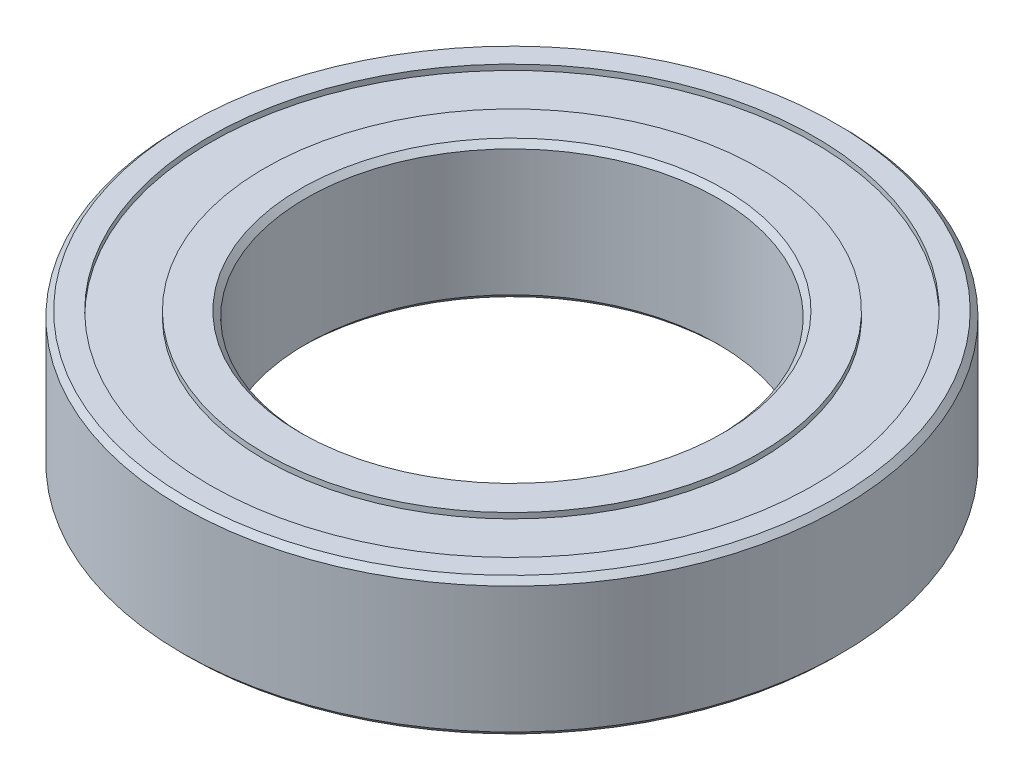
SolidWorks part; units mm, degrees
ref_plane "Front Plane" through (0, 0, 0) normal (0, 0, 1) x (1, 0, 0)
ref_plane "Top Plane" through (0, 0, 0) normal (0, 1, 0) x (1, 0, 0)
ref_plane "Right Plane" through (0, 0, 0) normal (1, 0, 0) x (0, 0, -1)
sketch "Sketch1" plane through (0, 0, 0) normal (0, 1, 0) x (1, 0, 0)
  circle A0 centre (0, 0) radius 12
  circle A1 centre (0, 0) radius 7.5
  dimension "D1" = 24
  dimension "D2" = 15
extrude "Boss-Extrude1" add sketch "Sketch1" along normal blind 5
sketch "Sketch2" plane through (0, 5, 0) normal (0, 1, 0) x (1, 0, 0)
  circle A0 centre (0, 0) radius 9
  circle A1 centre (0, 0) radius 11
  dimension "D1" = 22
  dimension "D2" = 18
extrude "Cut-Extrude1" cut sketch "Sketch2" against normal blind 0.2
sketch "Sketch3" plane through (0, 0, 0) normal (0, -1, 0) x (1, 0, 0)
  circle A0 centre (0, 0) radius 9 construction
  circle A1 centre (0, 0) radius 11
  circle A2 centre (0, 0) radius 11
  circle A3 centre (0, 0) radius 9
  dimension "D1" = 0
extrude "Cut-Extrude2" cut sketch "Sketch3" against normal blind 0.2
chamfer "Chamfer1" distance 0.2 angle 45 4 edges at (0, 5, 12) (0, 0, 12) (0, 5, 7.5) (0, 0, 7.5)
